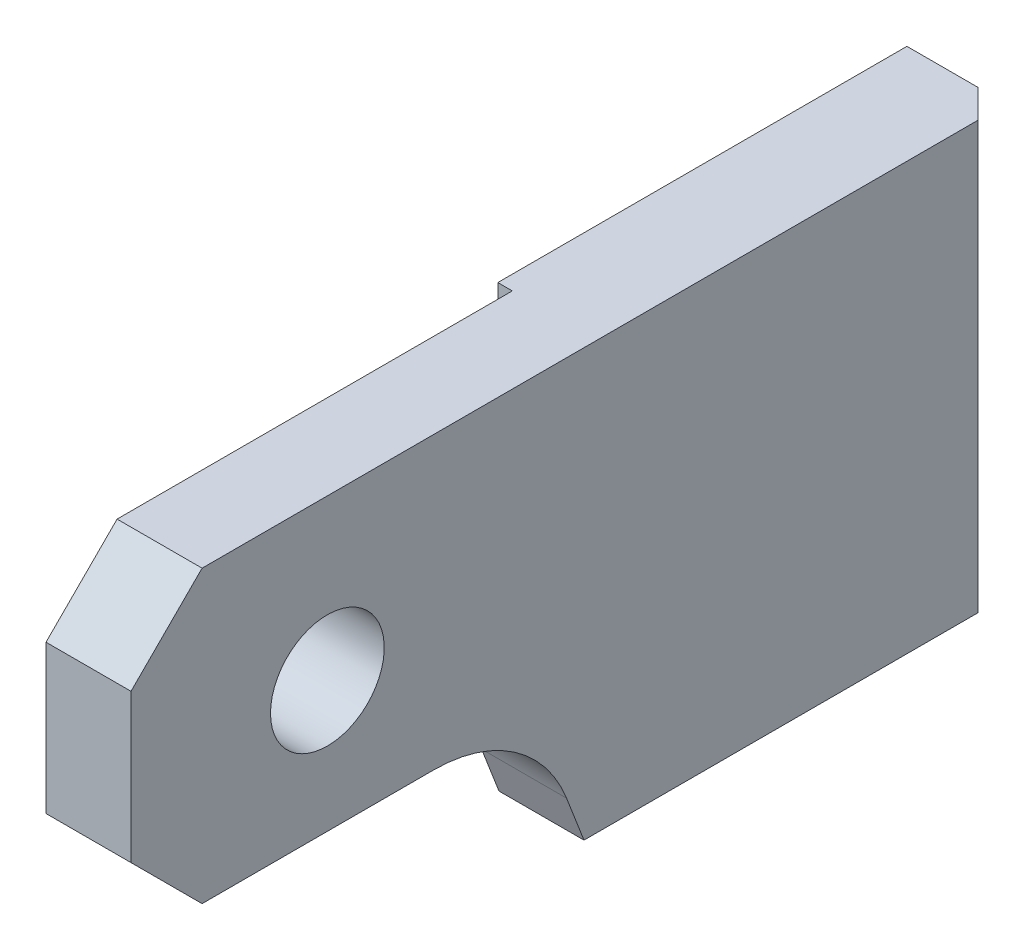
SolidWorks part; units mm, degrees
ref_plane "Спереди" through (0, 0, 0) normal (0, 0, 1) x (1, 0, 0)
ref_plane "Сверху" through (0, 0, 0) normal (0, 1, 0) x (1, 0, 0)
ref_plane "Справа" through (0, 0, 0) normal (1, 0, 0) x (0, 0, -1)
sketch "Эскиз1" plane through (0, 0, 0) normal (1, 0, 0) x (0, 0, -1)
  line L0 (62.8227, -30.8913) -> (59.12, -21.3277)
  line L1 (92.5393, -0.8884) -> (30.9567, -0.8884)
  line L2 (92.5393, -0.8884) -> (92.5393, -30.8968)
  line L3 (62.8227, -30.8913) -> (92.5393, -30.8968)
  line L4 (30.9567, -0.8884) -> (30.9567, -21.3277)
  line L5 (59.12, -21.3277) -> (30.9567, -21.3277)
extrude "Вытянуть1" add sketch "Эскиз1" against normal blind 7
fillet "Скругление1" radius 10 1 edges at (-3.5, -21.3277, -59.12)
chamfer "Фаска1" distance 5 angle 45 2 edges at (-3.5, -0.8884, -30.9567) (-3.5, -21.3277, -30.9567)
chamfer "Фаска2" distance 2 angle 45 1 edges at (0, -15.8926, -92.5393)
sketch "Эскиз3" plane through (-7, 0, 0) normal (-1, 0, 0) x (0, 0, 1)
  circle A0 centre (-44.7703, -12.1319) radius 4
extrude "Вырез-Вытянуть2" cut sketch "Эскиз3" against normal through all
sketch "Эскиз5" plane through (0, -30.8797, 0.0057) normal (0, -1, 0.0002) x (1, 0, 0)
  line L0 (-27.0843, -63.7597) -> (35.0361, -63.7597) construction
  line L1 (-7, -30.9597) -> (0, -30.9597) construction
  line L2 (-7, -35.9607) -> (-7, -52.2722) construction
  line L3 (-13.2889, -28.4631) -> (-5.98, -28.4631)
  line L4 (-13.2889, -28.4631) -> (-13.2889, -63.7597)
  line L5 (-13.2889, -63.7597) -> (-5.98, -63.7597)
  line L6 (-5.98, -28.4631) -> (-5.98, -63.7597)
  dimension "D1" = 32.8
  dimension "D2" = 1.02
extrude "Вытянуть2" cut sketch "Эскиз5" against normal through all
